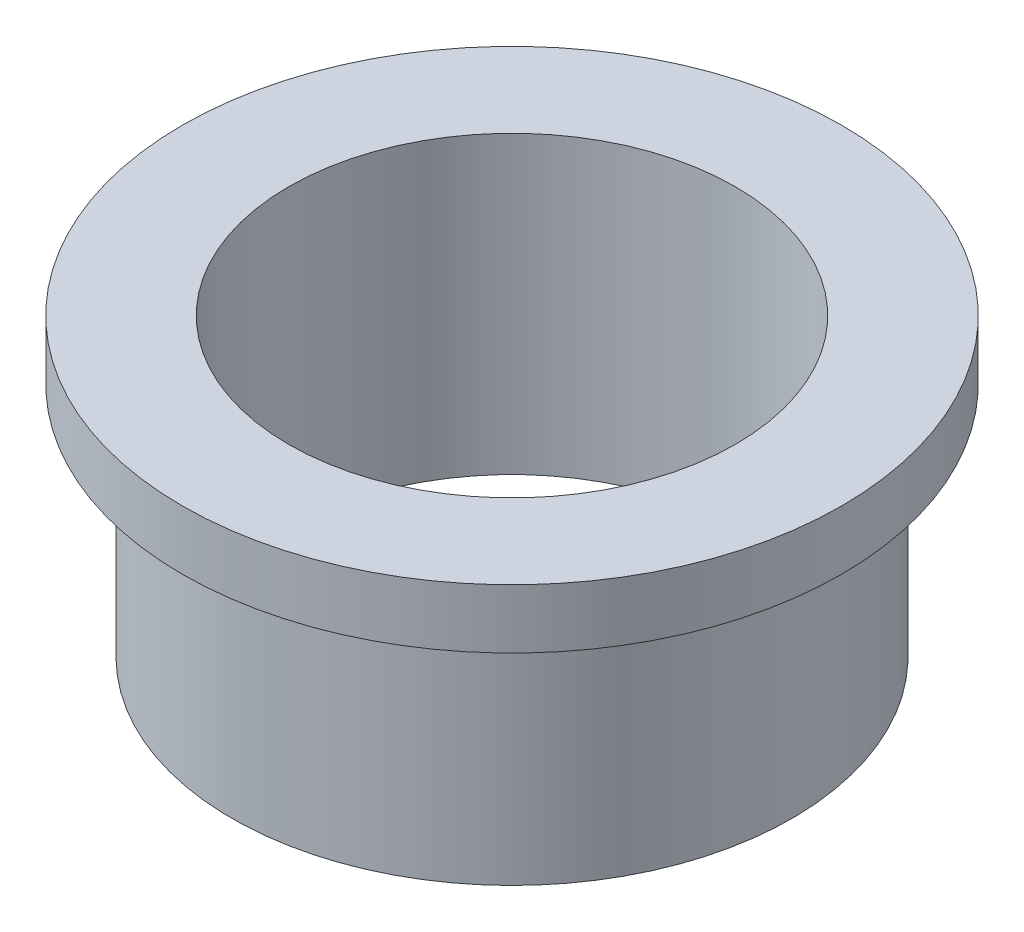
SolidWorks part; units mm, degrees
ref_plane "Front Plane" through (0, 0, 0) normal (0, 0, 1) x (1, 0, 0)
ref_plane "Top Plane" through (0, 0, 0) normal (0, 1, 0) x (1, 0, 0)
ref_plane "Right Plane" through (0, 0, 0) normal (1, 0, 0) x (0, 0, -1)
sketch "Sketch1" plane through (0, 0, 0) normal (0, 0, 1) x (1, 0, 0)
  line L0 (1.525, 5.6) -> (1.31, 5.9724)
  line L1 (0, 0) -> (1.525, 0)
  line L2 (0, 0) -> (0, 5.6)
  line L3 (0, 5.6) -> (1.525, 5.6)
  line L4 (1.525, 0) -> (1.525, 5.6)
  line L5 (1.31, 5.9724) -> (1.31, 6.3524)
  line L6 (1.31, 6.3524) -> (2.86, 6.3524)
  line L7 (2.86, 6.3524) -> (2.86, 7.9424)
  line L8 (2.86, 7.9424) -> (0, 7.9424)
  line L9 (0, 7.9424) -> (0, 0)
  line L10 (-6, 0) -> (-6, 7.9424)
  dimension "D7" = 2.86
  dimension "D1" = 5.6
  dimension "D2" = 150
  dimension "D3" = 0.43
  dimension "D4" = 0.38
  dimension "D5" = 1.55
  dimension "D6" = 1.59
  dimension "D8" = 6
revolve "Revolve1" add sketch "Sketch1" angle 360 about L10
fillet "Fillet1" radius 0.25 1 edges at (-6, 6.3524, -7.31)
